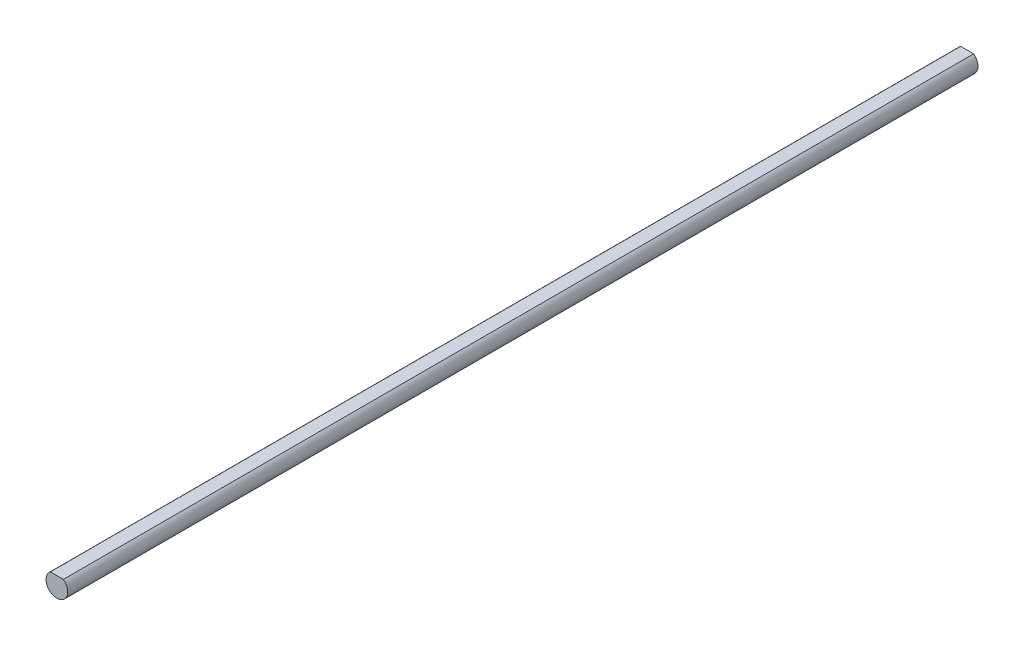
SolidWorks part; units mm, degrees
ref_plane "Front Plane" through (0, 0, 0) normal (0, 0, 1) x (1, 0, 0)
ref_plane "Top Plane" through (0, 0, 0) normal (0, 1, 0) x (1, 0, 0)
ref_plane "Right Plane" through (0, 0, 0) normal (1, 0, 0) x (0, 0, -1)
sketch "Sketch2" plane through (0, 0, 0) normal (0, 0, 1) x (1, 0, 0)
  circle A0 centre (0, 0) radius 3.175
  dimension "D1" = 6.35
extrude "Boss-Extrude1" add sketch "Sketch2" along normal blind 265.8872
sketch "Sketch3" plane through (0, 0, 265.8872) normal (0, 0, 1) x (1, 0, 0)
  line L1 (-3.4021, 3.175) -> (3.4638, 3.175)
  line L2 (-3.4021, 3.175) -> (-3.4021, 2.54)
  line L3 (-3.4021, 2.54) -> (3.4638, 2.54)
  line L4 (3.4638, 3.175) -> (3.4638, 2.54)
  dimension "D1" = 3.175
  dimension "D2" = 0.635
extrude "Cut-Extrude1" cut sketch "Sketch3" against normal up to surface (265.8872 mm away) up to face at (3.175, 0, 0)
